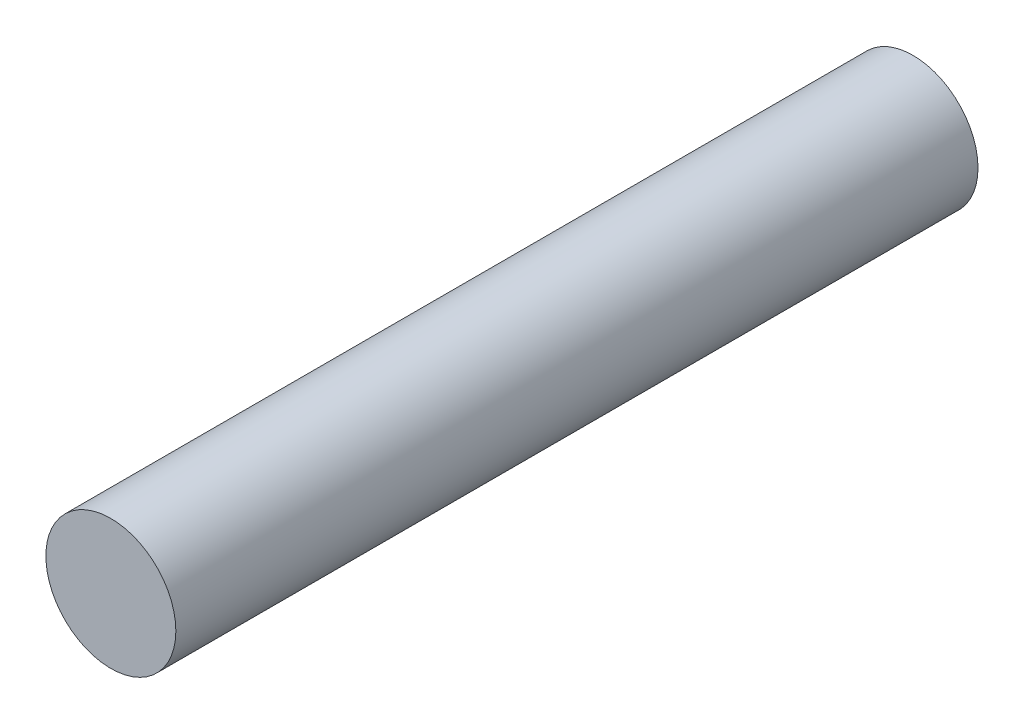
SolidWorks part; units mm, degrees
ref_plane "Front Plane" through (0, 0, 0) normal (0, 0, 1) x (1, 0, 0)
ref_plane "Top Plane" through (0, 0, 0) normal (0, 1, 0) x (1, 0, 0)
ref_plane "Right Plane" through (0, 0, 0) normal (1, 0, 0) x (0, 0, -1)
sketch "Sketch1" plane through (0, 0, 0) normal (0, 0, 1) x (1, 0, 0)
  circle A0 centre (0, 0) radius 0.175
  dimension "D1" = 0.35
extrude "Boss-Extrude1" add sketch "Sketch1" along normal blind 2.16
